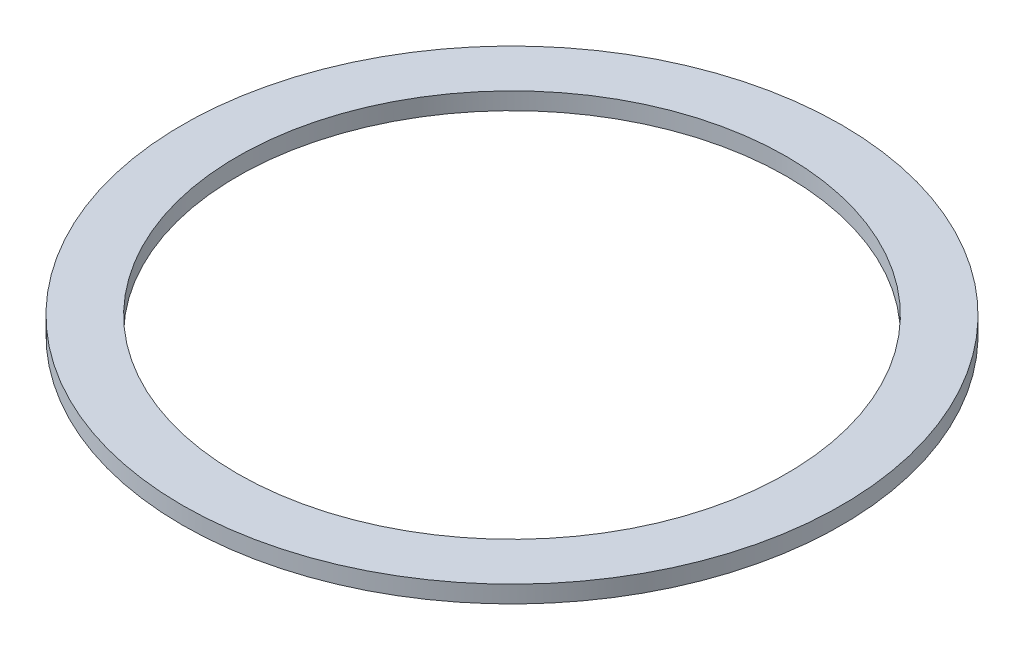
SolidWorks part; units mm, degrees
material "POM Acetal Copolymer"
ref_plane "Front Plane" through (0, 0, 0) normal (0, 0, 1) x (1, 0, 0)
ref_plane "Top Plane" through (0, 0, 0) normal (0, 1, 0) x (1, 0, 0)
ref_plane "Right Plane" through (0, 0, 0) normal (1, 0, 0) x (0, 0, -1)
sketch "Sketch1" plane through (0, 0, 0) normal (0, 1, 0) x (1, 0, 0)
  circle A0 centre (0, 0) radius 80
  circle A1 centre (0, 0) radius 96
  dimension "D1" = 160
  dimension "D2" = 192
extrude "Boss-Extrude1" add sketch "Sketch1" along normal blind 5
